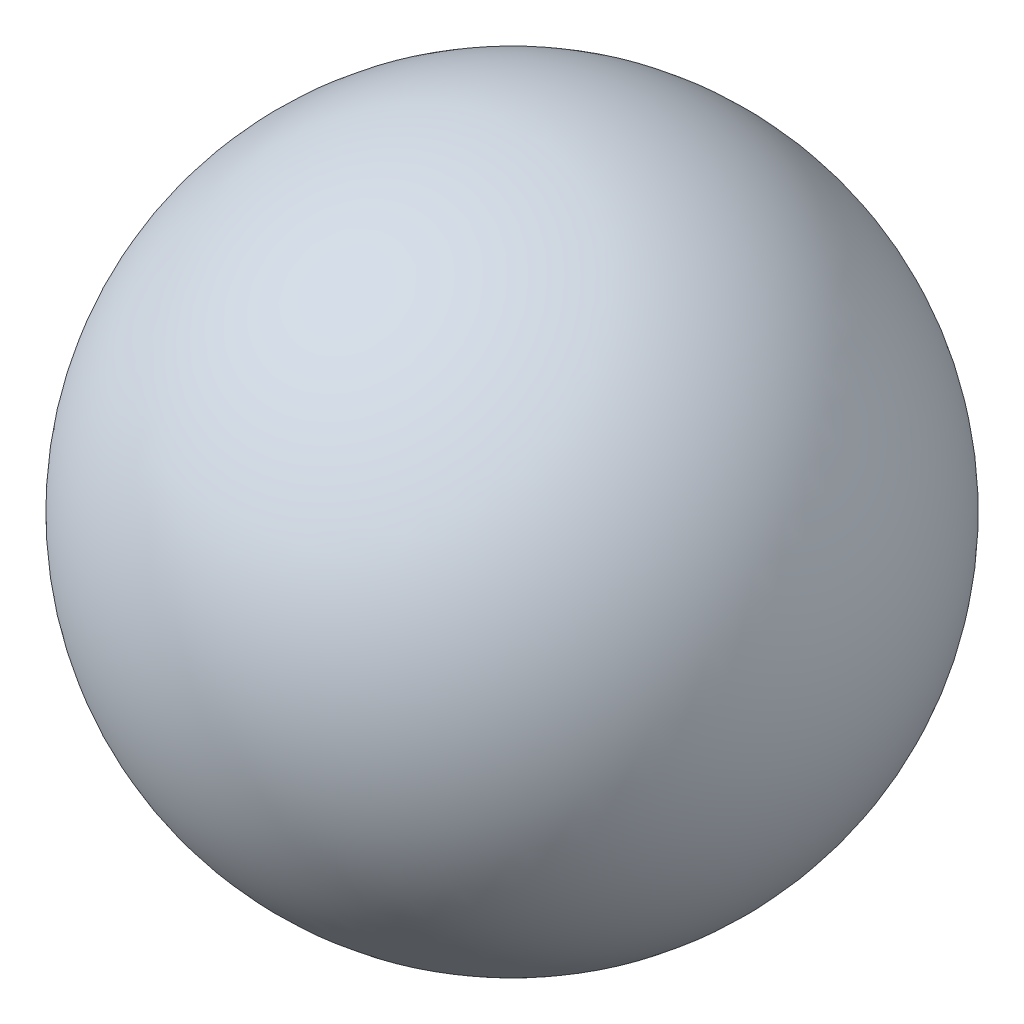
SolidWorks part; units mm, degrees
ref_plane "Front Plane" through (0, 0, 0) normal (0, 0, 1) x (1, 0, 0)
ref_plane "Top Plane" through (0, 0, 0) normal (0, 1, 0) x (1, 0, 0)
ref_plane "Right Plane" through (0, 0, 0) normal (1, 0, 0) x (0, 0, -1)
sketch "Sketch1" plane through (0, 0, 0) normal (0, 0, 1) x (1, 0, 0)
  line L0 (0, 2.75) -> (0, -2.75)
  arc A0 (0, -2.75) -> (0, 2.75) centre (0, 0) ccw
  dimension "D1" = 5.5
revolve "Revolve2" add sketch "Sketch1" angle 360 about L0
